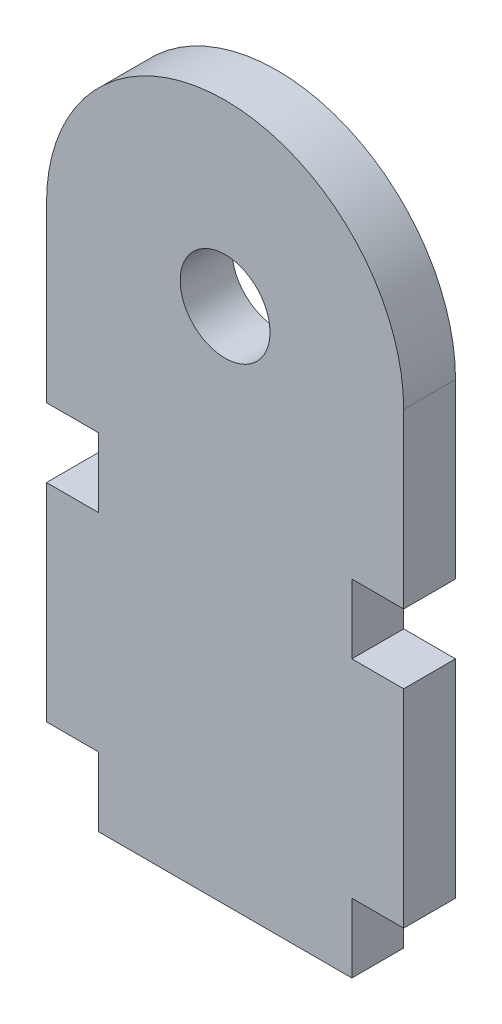
SolidWorks part; units mm, degrees
ref_plane "Plan de face" through (0, 0, 0) normal (0, 0, 1) x (1, 0, 0)
ref_plane "Plan de dessus" through (0, 0, 0) normal (0, 1, 0) x (1, 0, 0)
ref_plane "Plan de droite" through (0, 0, 0) normal (1, 0, 0) x (0, 0, -1)
sketch "Esquisse1" plane through (0, 0, 0) normal (0, 0, 1) x (1, 0, 0)
  line L0 (-27.86, -55) -> (-27.86, -75)
  line L1 (-27.86, -75) -> (45.53, -75)
  line L2 (-42.86, -55) -> (-42.86, 5)
  line L3 (60.53, 5) -> (45.53, 5)
  line L4 (60.53, -55) -> (60.53, 5)
  line L7 (60.53, -55) -> (45.53, -55)
  line L8 (-42.86, -55) -> (-27.86, -55)
  line L9 (8.835, 75) -> (8.835, -75) construction
  line L11 (60.53, 5) -> (45.53, 5)
  line L12 (60.53, 25) -> (45.53, 25)
  line L13 (45.53, 5) -> (45.53, 25)
  line L14 (45.53, -55) -> (45.53, -75)
  line L15 (60.53, 25) -> (60.53, 75)
  line L16 (-42.86, 5) -> (-27.86, 5)
  line L17 (-42.86, 25) -> (-27.86, 25)
  line L18 (-27.86, 5) -> (-27.86, 25)
  line L19 (-42.86, 25) -> (-42.86, 75)
  arc A0 (60.53, 75) -> (-42.86, 75) centre (8.835, 75) ccw
  circle A1 centre (8.835, 75) radius 13
  point P0 (0, 0)
  dimension "D3" = 60
  dimension "D9" = 26
  dimension "D1" = 103.39
  dimension "D4" = 20
  dimension "D5" = 20
  dimension "D6" = 15
  dimension "D7" = 15
extrude "Boss.-Extru.1" add sketch "Esquisse1" along normal blind 15 contours L11 L13 L12 L15 A0 L19 L17 L18 L16 L2 L8 L0 L1 L14 L7 L4 | A1
